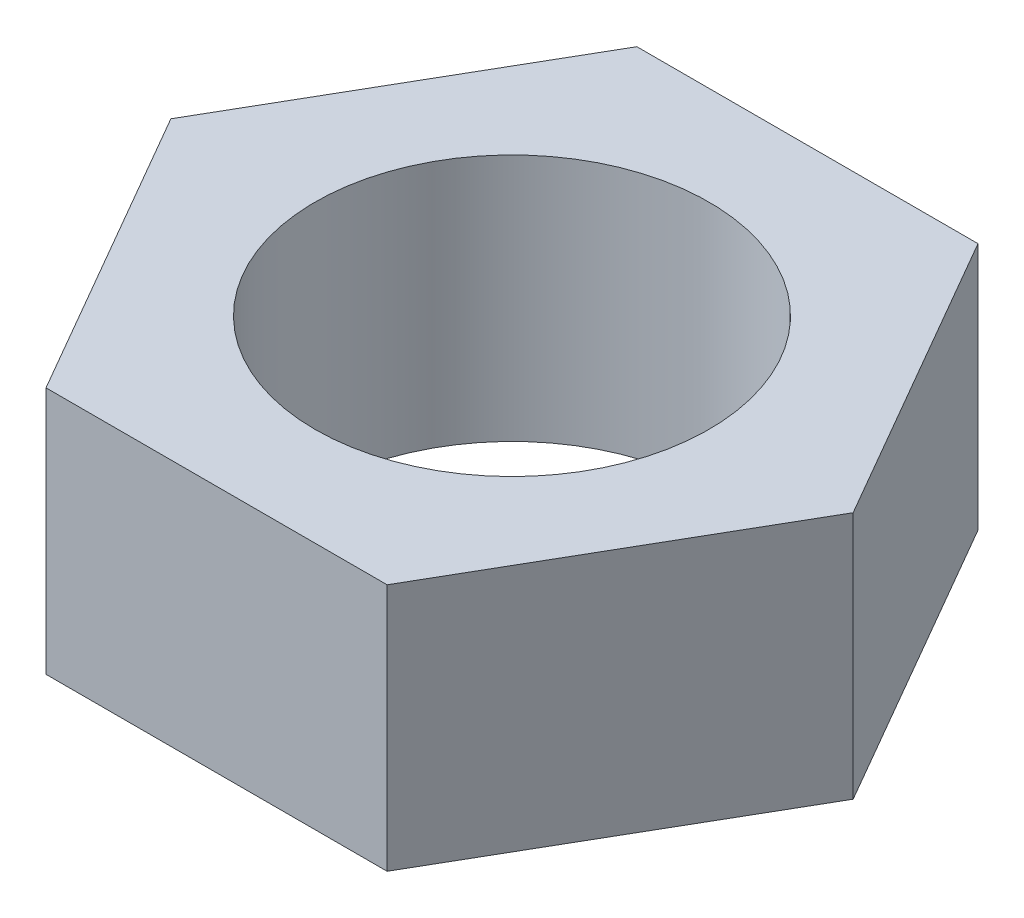
SolidWorks part; units mm, degrees
material "1060 Alloy"
ref_plane "Front Plane" through (0, 0, 0) normal (0, 0, 1) x (1, 0, 0)
ref_plane "Top Plane" through (0, 0, 0) normal (0, 1, 0) x (1, 0, 0)
ref_plane "Right Plane" through (0, 0, 0) normal (1, 0, 0) x (0, 0, -1)
sketch "Sketch1" plane through (0, 0, 0) normal (0, 1, 0) x (1, 0, 0)
  line L1 (2.7496, 0) -> (1.3748, 2.3813)
  line L2 (1.3748, 2.3813) -> (-1.3748, 2.3813)
  line L3 (-1.3748, 2.3813) -> (-2.7496, 0)
  line L4 (-2.7496, 0) -> (-1.3748, -2.3813)
  line L5 (-1.3748, -2.3813) -> (1.3748, -2.3813)
  line L6 (1.3748, -2.3813) -> (2.7496, 0)
  circle A0 centre (0, 0) radius 1.5875
  circle A1 centre (0, 0) radius 2.3812 construction
  dimension "D1" = 3.175
  dimension "D2" = 4.7625
extrude "Boss-Extrude1" add sketch "Sketch1" along normal blind 2
